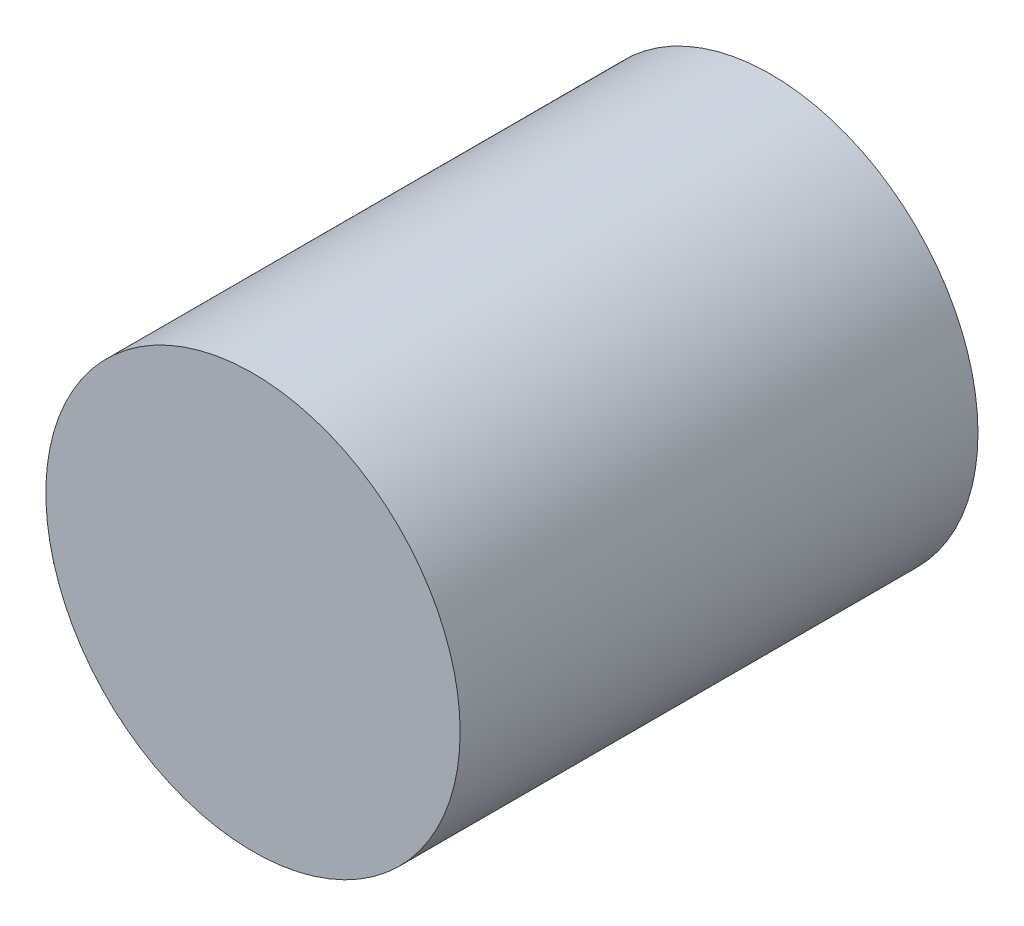
SolidWorks part; units mm, degrees
ref_plane "Front Plane" through (0, 0, 0) normal (0, 0, 1) x (1, 0, 0)
ref_plane "Top Plane" through (0, 0, 0) normal (0, 1, 0) x (1, 0, 0)
ref_plane "Right Plane" through (0, 0, 0) normal (1, 0, 0) x (0, 0, -1)
sketch "Sketch1" plane through (0, 0, 0) normal (0, 0, 1) x (1, 0, 0)
  circle A0 centre (0, 0) radius 80
  dimension "D1" = 160
extrude "Boss-Extrude1" add sketch "Sketch1" along normal blind 200
sketch "Sketch2" plane through (0, 0, 0) normal (0, 0, -1) x (-1, 0, 0)
  circle A0 centre (0, 0) radius 44
  dimension "D1" = 88
extrude "Boss-Extrude2" add sketch "Sketch2" along normal blind 14
sketch "Sketch3" plane through (0, 0, -14) normal (0, 0, -1) x (-1, 0, 0)
  circle A0 centre (0, 0) radius 30
  dimension "D1" = 60
extrude "Boss-Extrude3" add sketch "Sketch3" along normal blind 7
sketch "Sketch4" plane through (0, 0, -21) normal (0, 0, -1) x (-1, 0, 0)
  circle A0 centre (0, 0) radius 21.5
  dimension "D1" = 43
extrude "Cut-Extrude1" cut sketch "Sketch4" against normal blind 7
